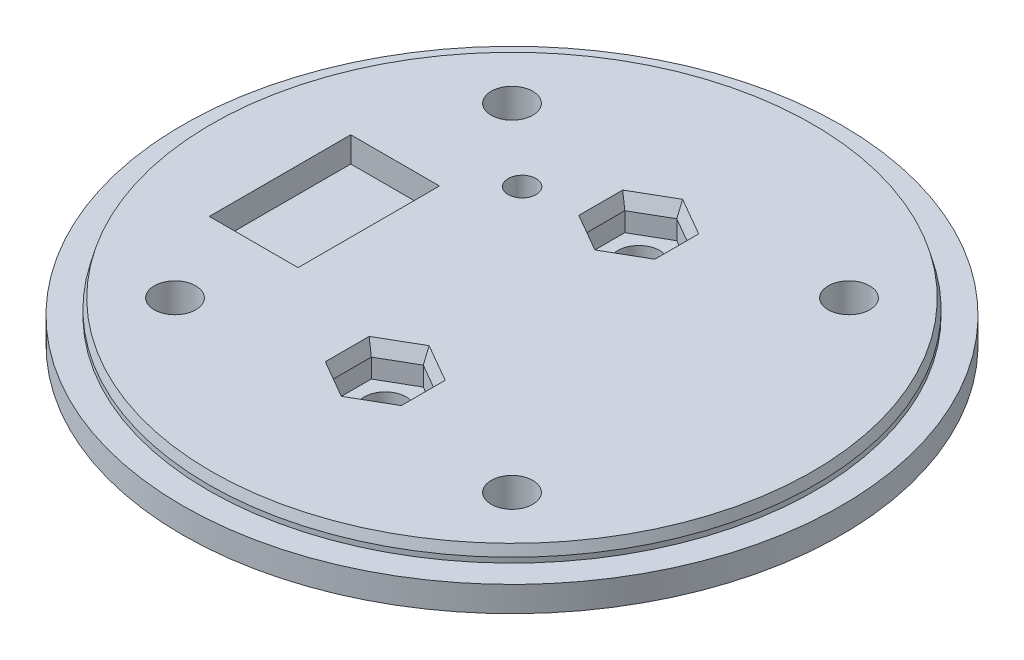
SolidWorks part; units mm, degrees
ref_plane "Спереди" through (0, 0, 0) normal (0, 0, 1) x (1, 0, 0)
ref_plane "Сверху" through (0, 0, 0) normal (0, 1, 0) x (1, 0, 0)
ref_plane "Справа" through (0, 0, 0) normal (1, 0, 0) x (0, 0, -1)
sketch "Эскиз1" plane through (0, 0, 0) normal (0, 1, 0) x (1, 0, 0)
  circle A0 centre (0, 0) radius 65
  dimension "D1" = 130
extrude "Бобышка-Вытянуть1" add sketch "Эскиз1" along normal blind 5
sketch "Эскиз2" plane through (0, 5, 0) normal (0, 1, 0) x (1, 0, 0)
  circle A0 centre (0, 0) radius 59.85
  dimension "D1" = 119.7
extrude "Бобышка-Вытянуть2" add sketch "Эскиз2" along normal blind 3
sketch "Эскиз3" plane through (0, 0, 0) normal (0, -1, 0) x (1, 0, 0)
  line L1 (17.5, -15) -> (-17.5, -15)
  line L2 (17.5, -15) -> (17.5, 15)
  line L3 (17.5, 15) -> (-17.5, 15)
  line L4 (-17.5, -15) -> (-17.5, 15)
  line L5 (17.5, -15) -> (-17.5, 15) construction
  line L6 (17.5, 15) -> (-17.5, -15) construction
  point P0 (0, 0)
  dimension "D1" = 35
  dimension "D2" = 30
extrude "Бобышка-Вытянуть3" add sketch "Эскиз3" along normal blind 25
sketch "Эскиз5" plane through (0, 0, 0) normal (0, -1, 0) x (1, 0, 0)
  line L1 (33.234, -33.234) -> (-33.234, -33.234) construction
  line L2 (33.234, -33.234) -> (33.234, 33.234) construction
  line L3 (33.234, 33.234) -> (-33.234, 33.234) construction
  line L4 (-33.234, -33.234) -> (-33.234, 33.234) construction
  line L5 (33.234, -33.234) -> (-33.234, 33.234) construction
  line L6 (33.234, 33.234) -> (-33.234, -33.234) construction
  circle A1 centre (33.234, -33.234) radius 4.1
  circle A2 centre (-33.234, -33.234) radius 4.1
  circle A3 centre (-33.234, 33.234) radius 4.1
  circle A4 centre (33.234, 33.234) radius 4.1
  circle A5 centre (0, 0) radius 47 construction
  point P0 (0, 0)
  dimension "D1" = 94
  dimension "D2" = 8.2
extrude "Вырез-Вытянуть2" cut sketch "Эскиз5" against normal through all
sketch "Эскиз6" plane through (0, 8, 0) normal (0, 1, 0) x (1, 0, 0)
  line L0 (0, 0) -> (0, 52.4) construction
  line L1 (0, 20) -> (-18, 20) construction
  circle A0 centre (0, 0) radius 59.85 construction
  circle A1 centre (-18, 20) radius 2.75
  dimension "D3" = 5.5
  dimension "D1" = 20
  dimension "D2" = 18
extrude "Вырез-Вытянуть3" cut sketch "Эскиз6" against normal through all
sketch "Sketch2" plane through (-17.5, 0, 0) normal (-1, 0, 0) x (0, 0, 1)
  line L0 (-15, -25) -> (15, 0) construction
  line L2 (10.125, -17.675) -> (-10.125, -17.675)
  line L3 (10.125, -17.675) -> (10.125, -7.325)
  line L4 (10.125, -7.325) -> (-10.125, -7.325)
  line L5 (-10.125, -17.675) -> (-10.125, -7.325)
  line L6 (10.125, -17.675) -> (-10.125, -7.325) construction
  line L7 (10.125, -7.325) -> (-10.125, -17.675) construction
  point P2 (0, -12.5)
  point P10 (0, -12.5)
  dimension "D1" = 20.25
  dimension "D2" = 10.35
extrude "Cut-Extrude1" cut sketch "Sketch2" against normal through all
chamfer "Chamfer1" distance 2 angle 15 1 edges at (0, 8, 59.85)
sketch "Sketch4" plane through (0, -25, 0) normal (0, -1, 0) x (1, 0, 0)
  line L0 (-17.5, 0) -> (17.5, 0) construction
  line L1 (-17.5, 15) -> (-17.5, -15) construction
  line L2 (17.5, -15) -> (17.5, 15) construction
  line L4 (17.5, -15) -> (-17.5, -15)
  line L5 (17.5, -15) -> (17.5, 15)
  line L6 (17.5, 15) -> (-17.5, 15)
  line L7 (-17.5, -15) -> (-17.5, 15)
  line L8 (17.5, -15) -> (-17.5, 15) construction
  line L9 (17.5, 15) -> (-17.5, -15) construction
  point P6 (0, 0)
extrude "Cut-Extrude3" cut sketch "Sketch4" against normal blind 12.5
sketch "Sketch5" plane through (0, -7.325, 0) normal (0, -1, 0) x (1, 0, 0)
  line L0 (0, 10.125) -> (0, -10.125) construction
  line L1 (17.5, 10.125) -> (-17.5, 10.125) construction
  line L2 (17.5, -10.125) -> (-17.5, -10.125) construction
  line L4 (10, -35) -> (-10, -35)
  line L5 (10, -35) -> (10, 35)
  line L6 (10, 35) -> (-10, 35)
  line L7 (-10, -35) -> (-10, 35)
  line L8 (10, -35) -> (-10, 35) construction
  line L9 (10, 35) -> (-10, -35) construction
  point P6 (0, 0)
  dimension "D1" = 20
  dimension "D2" = 70
extrude "Boss-Extrude2" add sketch "Sketch5" against normal up to surface (5.325 mm away) from offset 2 up to face at (-18, 0, -17.25) offset against normal yes
sketch "Sketch6" plane through (0, -5.325, 0) normal (0, -1, 0) x (1, 0, 0)
  line L0 (10, 25) -> (-10, 25) construction
  line L1 (10, 15) -> (10, 35) construction
  line L2 (-10, 35) -> (-10, 15) construction
  line L3 (10, -25) -> (-10, -25) construction
  line L4 (10, -35) -> (10, -15) construction
  line L5 (-10, -15) -> (-10, -35) construction
  circle A0 centre (0, 25) radius 4.15
  circle A1 centre (0, -25) radius 4.15
  dimension "D3" = 8.3
  dimension "D1" = 10
  dimension "D2" = 10
  dimension "D4" = 25
extrude "Cut-Extrude4" cut sketch "Sketch6" against normal through all
sketch "Sketch7" plane through (0, 8, 0) normal (0, 1, 0) x (1, 0, 0)
  line L1 (0, -32.5) -> (6.4952, -28.75)
  line L2 (6.4952, -28.75) -> (6.4952, -21.25)
  line L3 (6.4952, -21.25) -> (0, -17.5)
  line L4 (0, -17.5) -> (-6.4952, -21.25)
  line L5 (-6.4952, -21.25) -> (-6.4952, -28.75)
  line L6 (-6.4952, -28.75) -> (0, -32.5)
  line L7 (0, 17.5) -> (6.4952, 21.25)
  line L8 (6.4952, 21.25) -> (6.4952, 28.75)
  line L9 (6.4952, 28.75) -> (0, 32.5)
  line L10 (0, 32.5) -> (-6.4952, 28.75)
  line L11 (-6.4952, 28.75) -> (-6.4952, 21.25)
  line L12 (-6.4952, 21.25) -> (0, 17.5)
  circle A0 centre (0, -25) radius 7.5 construction
  circle A1 centre (0, 25) radius 7.5 construction
  dimension "D1" = 15
extrude "Cut-Extrude5" cut sketch "Sketch7" against normal blind 6.5
chamfer "Chamfer2" distance 1 angle 70 12 edges at (3.2476, 8, 19.375) (6.4952, 8, 25) (3.2476, 8, 30.625) (-3.2476, 8, 30.625) (-6.4952, 8, 25) (-3.2476, 8, 19.375) (3.2476, 8, -19.375) (6.4952, 8, -25) (3.2476, 8, -30.625) (-3.2476, 8, -30.625) (-6.4952, 8, -25) (-3.2476, 8, -19.375)
sketch "Sketch8" plane through (0, 8, 0) normal (0, 1, 0) x (1, 0, 0)
  line L1 (-26.25, 11.95) -> (-43.75, 11.95)
  line L2 (-26.25, 11.95) -> (-26.25, -15.95)
  line L3 (-26.25, -15.95) -> (-43.75, -15.95)
  line L4 (-43.75, 11.95) -> (-43.75, -15.95)
  line L5 (-26.25, 11.95) -> (-43.75, -15.95) construction
  line L6 (-26.25, -15.95) -> (-43.75, 11.95) construction
  point P0 (-35, -2)
  point P5 (-35, -12.2303)
  dimension "D1" = 27.9
  dimension "D2" = 17.5
  dimension "D3" = 35
  dimension "D4" = 2
extrude "Cut-Extrude6" cut sketch "Sketch8" against normal blind 5
